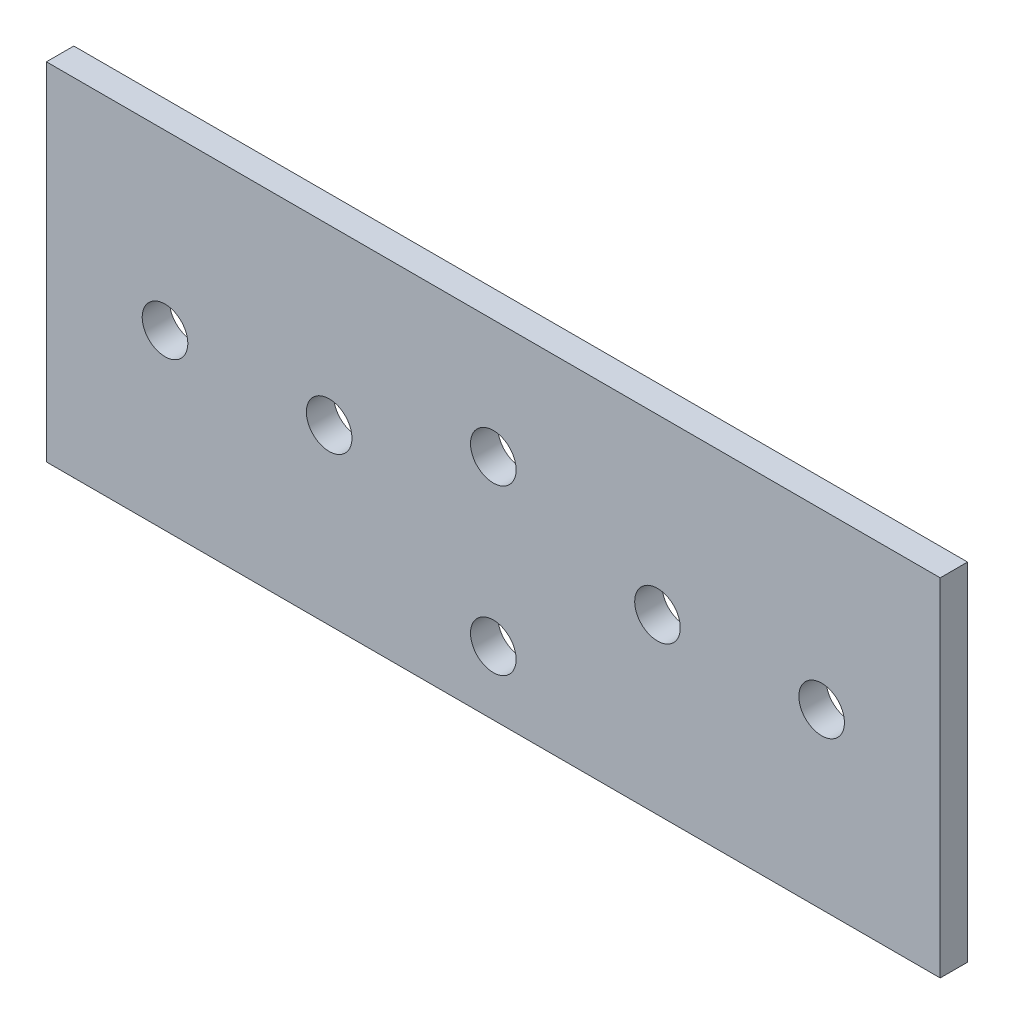
SolidWorks part; units mm, degrees
ref_plane "前基準面" through (0, 0, 0) normal (0, 0, 1) x (1, 0, 0)
ref_plane "上基準面" through (0, 0, 0) normal (0, 1, 0) x (1, 0, 0)
ref_plane "右基準面" through (0, 0, 0) normal (1, 0, 0) x (0, 0, -1)
sketch "草圖1" plane through (0, 0, 0) normal (0, 0, 1) x (1, 0, 0)
  line L1 (-49, 19) -> (49, 19)
  line L2 (-49, 19) -> (-49, -19)
  line L3 (-49, -19) -> (49, -19)
  line L4 (49, 19) -> (49, -19)
  line L5 (-49, 19) -> (49, -19) construction
  line L6 (-49, -19) -> (49, 19) construction
  point P0 (0, 0)
  dimension "D1" = 38
  dimension "D2" = 98
extrude "填料-伸長1" add sketch "草圖1" along normal blind 3
sketch "草圖2" plane through (0, 0, 0) normal (0, 0, -1) x (-1, 0, 0)
  line L0 (-49, -19) -> (-49, 19) construction
  circle A0 centre (-36, 0) radius 2.5
  circle A1 centre (-18, 0) radius 2.5
  dimension "D1" = 5
  dimension "D2" = 13
  dimension "D3" = 18
extrude "除料-伸長1" cut sketch "草圖2" against normal up to next
mirror "鏡射1" about plane through (0, 0, 0) normal (1, 0, 0) of "除料-伸長1"
sketch "草圖3" plane through (0, 0, 0) normal (0, 0, -1) x (-1, 0, 0)
  line L0 (49, -19) -> (-49, -19) construction
  circle A0 centre (0, -12) radius 2.5
  circle A1 centre (0, 6) radius 2.5
  dimension "D1" = 5
  dimension "D2" = 7
  dimension "D3" = 18
extrude "除料-伸長2" cut sketch "草圖3" against normal up to next
